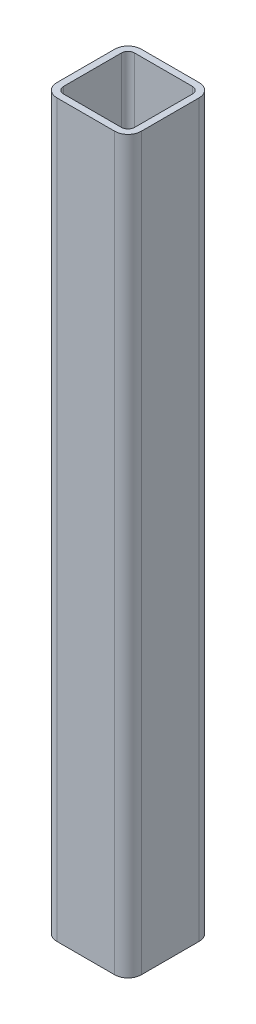
SolidWorks part; units mm, degrees
ref_plane "Front Plane" through (0, 0, 0) normal (0, 0, 1) x (1, 0, 0)
ref_plane "Top Plane" through (0, 0, 0) normal (0, 1, 0) x (1, 0, 0)
ref_plane "Right Plane" through (0, 0, 0) normal (1, 0, 0) x (0, 0, -1)
sketch3d "3DSketch1"
  line L0 (0, 0, 0) -> (0, 220, 0)
  dimension "D1" = 220
other "Square tube 20 X 20 X 2(1)"
ref_plane "Plane1" through (0, 0, 0) normal (0, 1, 0) x (1, 0, 0)
sketch "Sketch1" plane through (0, 0, 0) normal (0, 1, 0) x (1, 0, 0)
  line L0 (-8.7, -10.7) -> (8.7, -10.7)
  line L1 (-10.7, -8.7) -> (-10.7, 8.7)
  line L2 (8.7, 10.7) -> (-8.7, 10.7)
  line L3 (10.7, 8.7) -> (10.7, -8.7)
  line L4 (-8.7, -12.7) -> (8.7, -12.7)
  line L5 (-12.7, -8.7) -> (-12.7, 8.7)
  line L6 (8.7, 12.7) -> (-8.7, 12.7)
  line L7 (12.7, 8.7) -> (12.7, -8.7)
  arc A0 (12.7, 8.7) -> (8.7, 12.7) centre (8.7, 8.7) ccw
  arc A1 (8.7, -12.7) -> (12.7, -8.7) centre (8.7, -8.7) ccw
  arc A2 (-12.7, -8.7) -> (-8.7, -12.7) centre (-8.7, -8.7) ccw
  arc A3 (-8.7, 12.7) -> (-12.7, 8.7) centre (-8.7, 8.7) ccw
  arc A4 (-8.7, 10.7) -> (-10.7, 8.7) centre (-8.7, 8.7) ccw
  arc A5 (10.7, 8.7) -> (8.7, 10.7) centre (8.7, 8.7) ccw
  arc A6 (8.7, -10.7) -> (10.7, -8.7) centre (8.7, -8.7) ccw
  arc A7 (-10.7, -8.7) -> (-8.7, -10.7) centre (-8.7, -8.7) ccw
  point P0 (-12.7, 0)
  point P1 (12.7, 0)
  point P2 (0, 12.7)
  point P3 (0, -12.7)
  point P4 (0, 0)
  point P5 (-12.7, -12.7)
  point P6 (12.7, -12.7)
  point P7 (12.7, 12.7)
  point P8 (-12.7, 12.7)
  point P33 (0, 0)
  dimension "D1" = 4
  dimension "Thickness" = 2
  dimension "V_leg" = 25.4
